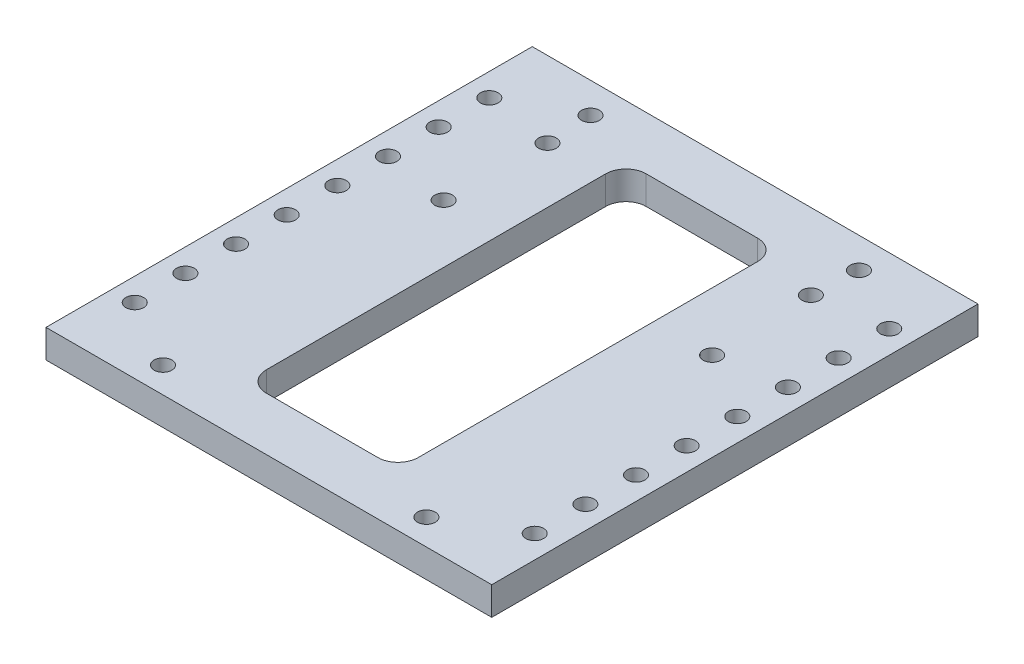
SolidWorks part; units mm, degrees
ref_plane "Front Plane" through (0, 0, 0) normal (0, 0, 1) x (1, 0, 0)
ref_plane "Top Plane" through (0, 0, 0) normal (0, 1, 0) x (1, 0, 0)
ref_plane "Right Plane" through (0, 0, 0) normal (1, 0, 0) x (0, 0, -1)
sketch "Sketch1" plane through (0, 0, 0) normal (0, 1, 0) x (1, 0, 0)
  line L1 (-42.0478, 45.1917) -> (45.9522, 45.1917)
  line L2 (-42.0478, 45.1917) -> (-42.0478, -50.8083)
  line L3 (-42.0478, -50.8083) -> (45.9522, -50.8083)
  line L4 (45.9522, 45.1917) -> (45.9522, -50.8083)
  dimension "D1" = 96
  dimension "D2" = 88
extrude "Boss-Extrude1" add sketch "Sketch1" along normal blind 5.588
sketch "Sketch3" plane through (0, 5.588, 0) normal (0, 1, 0) x (1, 0, 0)
  line L0 (-24.0478, 30.1917) -> (-24.0478, -45.7083) construction
  line L1 (-24.0478, -45.7083) -> (27.9522, -45.7083) construction
  line L2 (27.9522, -45.7083) -> (27.9522, 30.1917) construction
  line L3 (27.9522, 30.1917) -> (-24.0478, 30.1917) construction
  line L4 (-42.0478, -2.8083) -> (45.9522, -2.8083) construction
  line L5 (-42.0478, 45.1917) -> (-42.0478, -50.8083) construction
  line L6 (45.9522, -50.8083) -> (45.9522, 45.1917) construction
  line L7 (1.9522, -50.8083) -> (1.9522, 45.1917) construction
  line L8 (-42.0478, -50.8083) -> (45.9522, -50.8083) construction
  line L9 (45.9522, 45.1917) -> (-42.0478, 45.1917) construction
  line L10 (-24.5478, 10.1917) -> (-24.5478, 39.1917) construction
  line L11 (-24.5478, 39.1917) -> (28.4522, 39.1917) construction
  line L12 (28.4522, 39.1917) -> (28.4522, 10.1917) construction
  line L13 (28.4522, 10.1917) -> (-24.5478, 10.1917) construction
  circle A0 centre (-24.0478, 30.1917) radius 1.75
  circle A1 centre (27.9522, 30.1917) radius 1.75
  circle A2 centre (-24.0478, -45.7083) radius 1.75
  circle A3 centre (27.9522, -45.7083) radius 1.75
  circle A4 centre (-24.5478, 39.1917) radius 1.75
  circle A5 centre (28.4522, 39.1917) radius 1.75
  circle A6 centre (-24.5478, 10.1917) radius 1.75
  circle A7 centre (28.4522, 10.1917) radius 1.75
  dimension "D3" = 3.5
  dimension "D1" = 75.9
  dimension "D2" = 52
  dimension "D4" = 53
  dimension "D5" = 29
  dimension "D6" = 6
  dimension "D7" = 15
extrude "Cut-Extrude1" cut sketch "Sketch3" against normal through all
sketch "Sketch4" plane through (0, 5.588, 0) normal (0, 1, 0) x (1, 0, 0)
  line L0 (1.9522, 45.1917) -> (1.9522, -50.8083) construction
  line L1 (-9.0478, 34.6917) -> (12.9522, 34.6917)
  line L2 (-13.0478, 30.6917) -> (-13.0478, -36.3083)
  line L3 (-9.0478, -40.3083) -> (12.9522, -40.3083)
  line L4 (16.9522, 30.6917) -> (16.9522, -36.3083)
  line L5 (45.9522, 45.1917) -> (-42.0478, 45.1917) construction
  line L6 (-42.0478, -50.8083) -> (45.9522, -50.8083) construction
  line L7 (-42.0478, -2.8083) -> (45.9522, -2.8083) construction
  line L8 (-42.0478, 45.1917) -> (-42.0478, -50.8083) construction
  line L9 (45.9522, -50.8083) -> (45.9522, 45.1917) construction
  arc A0 (16.9522, -36.3083) -> (12.9522, -40.3083) centre (12.9522, -36.3083) cw
  arc A1 (-9.0478, -40.3083) -> (-13.0478, -36.3083) centre (-9.0478, -36.3083) cw
  arc A2 (16.9522, 30.6917) -> (12.9522, 34.6917) centre (12.9522, 30.6917) ccw
  arc A3 (-9.0478, 34.6917) -> (-13.0478, 30.6917) centre (-9.0478, 30.6917) ccw
  point P12 (16.9522, -40.3083)
  point P17 (16.9522, 34.6917)
  point P20 (-13.0478, 34.6917)
  dimension "D3" = 4
  dimension "D1" = 75
  dimension "D2" = 30
extrude "Cut-Extrude2" cut sketch "Sketch4" against normal through all
sketch "Sketch5" plane through (0, 5.588, 0) normal (0, 1, 0) x (1, 0, 0)
  line L0 (1.9522, 45.1917) -> (1.9522, -50.8083) construction
  line L1 (45.9522, 45.1917) -> (-42.0478, 45.1917) construction
  line L2 (-42.0478, -50.8083) -> (45.9522, -50.8083) construction
  line L3 (-42.0478, -2.8083) -> (45.9522, -2.8083) construction
  line L4 (-42.0478, 45.1917) -> (-42.0478, -50.8083) construction
  line L5 (45.9522, -50.8083) -> (45.9522, 45.1917) construction
  circle A0 centre (-37.5278, 32.1917) radius 1.75
  circle A1 centre (41.4322, 32.1917) radius 1.75
  circle A2 centre (-37.5278, 22.1917) radius 1.75
  circle A3 centre (41.4322, 22.1917) radius 1.75
  circle A4 centre (-37.5278, 12.1917) radius 1.75
  circle A5 centre (41.4322, 12.1917) radius 1.75
  circle A6 centre (-37.5278, 2.1917) radius 1.75
  circle A7 centre (41.4322, 2.1917) radius 1.75
  circle A8 centre (-37.5278, -7.8083) radius 1.75
  circle A9 centre (41.4322, -7.8083) radius 1.75
  circle A10 centre (-37.5278, -17.8083) radius 1.75
  circle A11 centre (41.4322, -17.8083) radius 1.75
  circle A12 centre (-37.5278, -27.8083) radius 1.75
  circle A13 centre (41.4322, -27.8083) radius 1.75
  circle A14 centre (-37.5278, -37.8083) radius 1.75
  circle A15 centre (41.4322, -37.8083) radius 1.75
  dimension "D1" = 3.5
  dimension "D2" = 78.96
  dimension "D4" = 10
  dimension "D3" = 8
extrude "Cut-Extrude3" cut sketch "Sketch5" against normal through all
